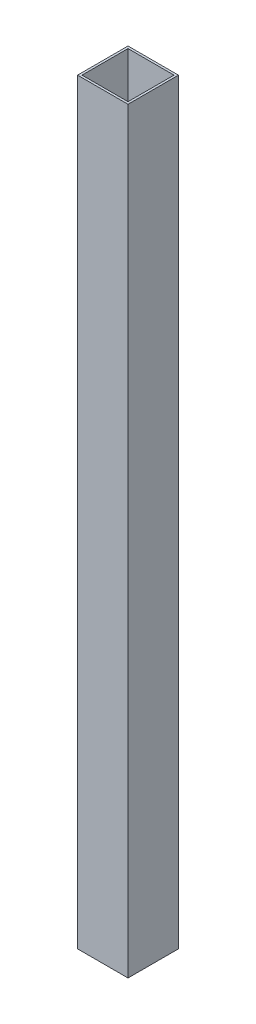
SolidWorks part; units mm, degrees
ref_plane "Front Plane" through (0, 0, 0) normal (0, 0, 1) x (1, 0, 0)
ref_plane "Top Plane" through (0, 0, 0) normal (0, 1, 0) x (1, 0, 0)
ref_plane "Right Plane" through (0, 0, 0) normal (1, 0, 0) x (0, 0, -1)
sketch "Sketch1" plane through (0, 0, 0) normal (0, 1, 0) x (1, 0, 0)
  line L0 (0, 0) -> (0, 50)
  line L1 (0, 50) -> (50, 50)
  line L2 (50, 50) -> (50, 0)
  line L3 (50, 0) -> (0, 0)
  line L4 (2.2, 47.8) -> (47.8, 47.8)
  line L5 (47.8, 47.8) -> (47.8, 2.2)
  line L6 (47.8, 2.2) -> (2.2, 2.2)
  line L7 (2.2, 2.2) -> (2.2, 47.8)
  dimension "D1" = 50
  dimension "D2" = 50
  dimension "D3" = 2.2
extrude "Boss-Extrude1" add sketch "Sketch1" along normal blind 750
equation "\"SquareTube_wheel_length\"= 750"
equation "\"D1@Boss-Extrude1\"= \"CarBeamWidth\" + 50"
equation "\"CarBeamWidth\"=700.0"
equation "\"MetalSheet_3mm_length\"=5030.0"
equation "\"MetalSheet_3mm_width\"=1923.0"
equation "\"MetalSheet_3mm_FloorCut_L_length\"=1764.0"
equation "\"MetalSheet_3mm_FloorCut_L_disdance\"=1665.0"
equation "\"MetalSheet_3mm_FloorCut_R_length\"=1764.0"
equation "\"MetalSheet_3mm_FloorCut_R_disdance\"=1665.0"
equation "\"indoorHeight\"=1940.0"
equation "\"x\"=66.0"
equation "\"da\"=62.0"
equation "\"SquareTube_length\"=1923.0"
equation "\"channelSteel_length\"=5030.0"
equation "\"SquareTube_inFront1_cutDepth50_R\"=0.5"
equation "\"SquareTube_inFront1_cutDepth50_L\"=0.5"
equation "\"SquareTube_inFront2_cutDepth50_R\"=0.5"
equation "\"SquareTube_inFront2_cutDepth50_L\"=0.5"
equation "\"SquareTube_inFront3_cutDepth50_R\"=0.5"
equation "\"SquareTube_inFront3_cutDepth50_L\"=0.5"
equation "\"SquareTube_inFront4_cutDepth50_R\"=0.5"
equation "\"SquareTube_inFront4_cutDepth50_L\"=0.5"
equation "\"SquareTube_inFront5_cutDepth50_R\"=50"
equation "\"SquareTube_inFront5_cutDepth50_L\"=50"
equation "\"SquareTube_inFront6_cutDepth50_R\"=50"
equation "\"SquareTube_inFront6_cutDepth50_L\"=50"
equation "\"SquareTube_inFront7_cutDepth50_R\"=50"
equation "\"SquareTube_inFront7_cutDepth50_L\"=50"
equation "\"SquareTube_inFront8_cutDepth50_R\"=50"
equation "\"SquareTube_inFront8_cutDepth50_L\"=50"
equation "\"SquareTube_inFront9_cutDepth50_R\"=50"
equation "\"SquareTube_inFront9_cutDepth50_L\"=50"
equation "\"SquareTube_inFront10_cutDepth50_R\"=50"
equation "\"SquareTube_inFront10_cutDepth50_L\"=50"
equation "\"SquareTube_inBack1_cutDepth50_R\"=50"
equation "\"SquareTube_inBack1_cutDepth50_L\"=50"
equation "\"SquareTube_inBack2_cutDepth50_R\"=50"
equation "\"SquareTube_inBack2_cutDepth50_L\"=50"
equation "\"SquareTube_inBack3_cutDepth50_R\"=50"
equation "\"SquareTube_inBack3_cutDepth50_L\"=50"
equation "\"SquareTube_inBack4_cutDepth50_R\"=50"
equation "\"SquareTube_inBack4_cutDepth50_L\"=50"
equation "\"SquareTube_inBack5_cutDepth50_R\"=50"
equation "\"SquareTube_inBack5_cutDepth50_L\"=50"
equation "\"SquareTube_inBack6_cutDepth50_R\"=0.5"
equation "\"SquareTube_inBack6_cutDepth50_L\"=0.5"
